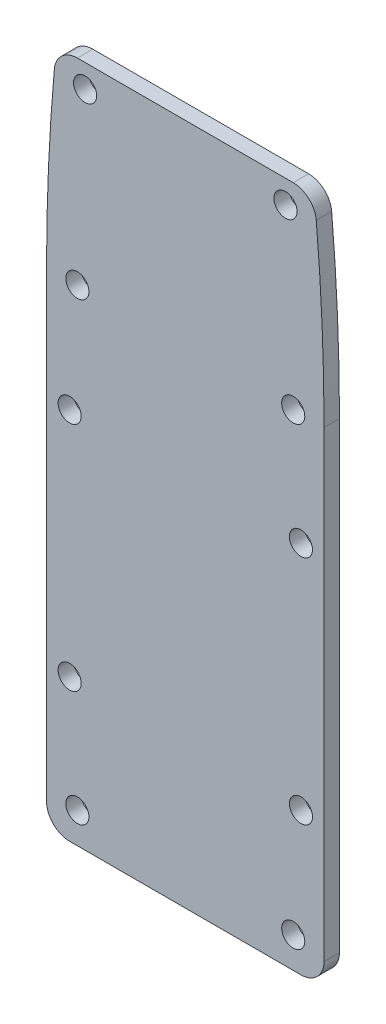
SolidWorks part; units mm, degrees
material "Carbon Fiber"
ref_plane "Front Plane" through (0, 0, 0) normal (0, 0, 1) x (1, 0, 0)
ref_plane "Top Plane" through (0, 0, 0) normal (0, 1, 0) x (1, 0, 0)
ref_plane "Right Plane" through (0, 0, 0) normal (1, 0, 0) x (0, 0, -1)
sketch "Sketch1" plane through (0, 0, 0) normal (0, 0, 1) x (1, 0, 0)
  line L0 (-14, 29.5) -> (14, -29.5) construction
  line L2 (-14, 29.5) -> (-14, -29.5) construction
  line L3 (-14, -29.5) -> (14, -29.5) construction
  line L4 (14, 29.5) -> (14, -29.5) construction
  line L5 (-18, 29.5) -> (-18, -33.5)
  line L6 (-18, -33.5) -> (18, -33.5)
  line L7 (18, 29.5) -> (18, -33.5)
  line L8 (-14, 52) -> (14, 52) construction
  line L9 (0, 0) -> (0, 52) construction
  line L10 (-14, 29.5) -> (-14, 52) construction
  line L11 (14, 29.5) -> (14, 52) construction
  line L12 (-14, 55) -> (14, 55)
  line L13 (14, 29.5) -> (14, 52) construction
  line L14 (0, 0) -> (25.8882, 25.8882) construction
  arc A0 (-18, 29.5) -> (-16.9882, 52.2661) centre (238.625, 29.5) cw
  arc A1 (-14, 55) -> (-16.9882, 52.2661) centre (-14, 52) ccw
  arc A4 (14, 55) -> (16.9882, 52.2661) centre (14, 52) cw
  arc A5 (18, 29.5) -> (16.9882, 52.2661) centre (-238.625, 29.5) ccw
  circle A6 centre (-14, 29.5) radius 1.5
  circle A7 centre (14, 29.5) radius 1.5
  circle A8 centre (-14, -29.5) radius 1.5
  circle A9 centre (14, -29.5) radius 1.5
  circle A10 centre (15, 15) radius 1.5
  circle A11 centre (15, -15) radius 1.5
  circle A12 centre (-15, -15) radius 1.5
  circle A13 centre (-15, 15) radius 1.5
  circle A14 centre (-13, 52) radius 1.5
  circle A15 centre (13, 52) radius 1.5
  point P23 (0, 55)
  point P38 (0, 0)
  dimension "D5" = 3
  dimension "D6" = 6
  dimension "D7" = 3
  dimension "D8" = 3
  dimension "D9" = 3
  dimension "D10" = 3
  dimension "D13" = 3
  dimension "D15" = 3
  dimension "D1" = 28
  dimension "D2" = 81.5
  dimension "D3" = 4
  dimension "D4" = 63
  dimension "D11" = 45
  dimension "D12" = 15
  dimension "D16" = 26
  dimension "D17" = 13
  dimension "D14" = 4
extrude "Boss-Extrude1" add sketch "Sketch1" along normal blind 2
fillet "Fillet1" radius 3 2 edges at (18, -33.5, 1) (-18, -33.5, 1)
